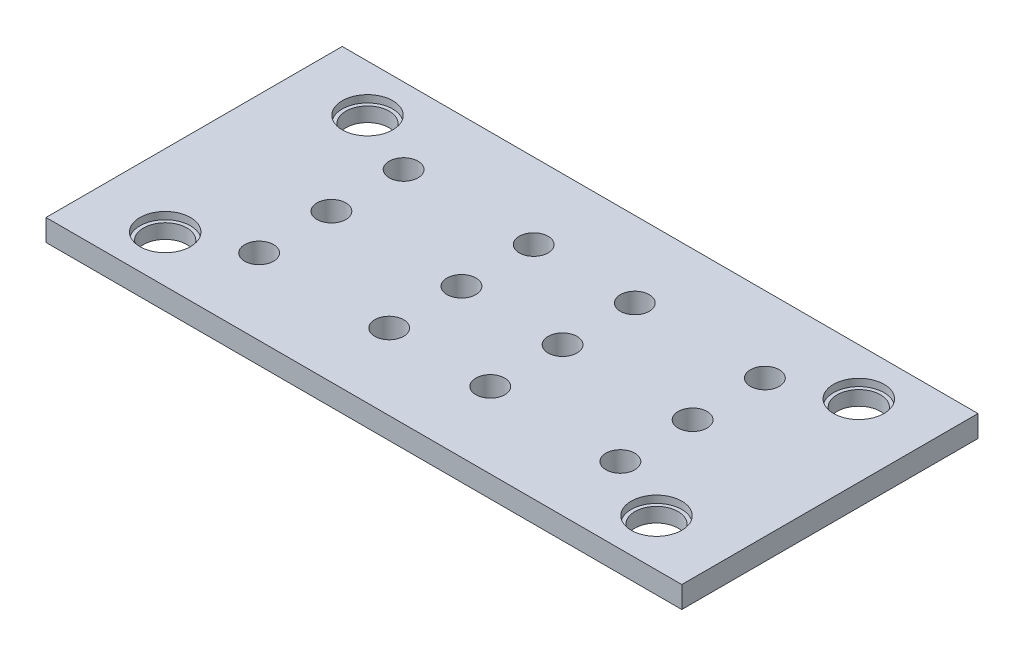
SolidWorks part; units mm, degrees
ref_plane "Front Plane" through (0, 0, 0) normal (0, 0, 1) x (1, 0, 0)
ref_plane "Top Plane" through (0, 0, 0) normal (0, 1, 0) x (1, 0, 0)
ref_plane "Right Plane" through (0, 0, 0) normal (1, 0, 0) x (0, 0, -1)
sketch "Sketch1" plane through (0, 0, 0) normal (0, 1, 0) x (1, 0, 0)
  line L1 (-440, 205) -> (440, 205)
  line L2 (-440, 205) -> (-440, -205)
  line L3 (-440, -205) -> (440, -205)
  line L4 (440, 205) -> (440, -205)
  line L5 (0, -205) -> (0, 205) construction
  line L6 (-440, 0) -> (440, 0) construction
  point P0 (0, 0)
extrude "Boss-Extrude1" add sketch "Sketch1" along normal blind 30
sketch "Sketch2" plane through (0, 30, 0) normal (0, 1, 0) x (1, 0, 0)
  circle A0 centre (-340, 140) radius 30
  circle A1 centre (340, 140) radius 30
  circle A2 centre (340, -140) radius 30
  circle A3 centre (-340, -140) radius 30
  dimension "D1" = 140
  dimension "D3" = 680
  dimension "D4" = 340
  dimension "D2" = 140
extrude "Cut-Extrude1" cut sketch "Sketch2" against normal blind 225
sketch "Sketch3" plane through (0, 30, 0) normal (0, 1, 0) x (1, 0, 0)
  circle A0 centre (-340, 140) radius 35
  circle A1 centre (-340, -540) radius 35
  circle A2 centre (-340, -820) radius 35
  circle A3 centre (-340, -140) radius 35
  circle A4 centre (340, 140) radius 35
  circle A5 centre (340, -140) radius 35
  dimension "D1" = 2
  dimension "D2" = 2
  dimension "D3" = 2
extrude "Cut-Extrude2" cut sketch "Sketch3" against normal blind 10
sketch "Sketch4" plane through (0, 30, 0) normal (0, 1, 0) x (1, 0, 0)
  circle A0 centre (-250, 0) radius 20
  circle A1 centre (-70, 0) radius 20
  circle A2 centre (-250, 100) radius 20
  circle A3 centre (-250, -100) radius 20
  circle A4 centre (-70, 100) radius 20
  circle A5 centre (-70, -100) radius 20
  circle A6 centre (70, -100) radius 20
  circle A7 centre (70, 100) radius 20
  circle A8 centre (250, -100) radius 20
  circle A9 centre (250, 100) radius 20
  circle A10 centre (70, 0) radius 20
  circle A11 centre (250, 0) radius 20
  dimension "D1" = 250
  dimension "D2" = 70
  dimension "D3" = 100
  dimension "D4" = 100
extrude "Cut-Extrude3" cut sketch "Sketch4" against normal blind 154
